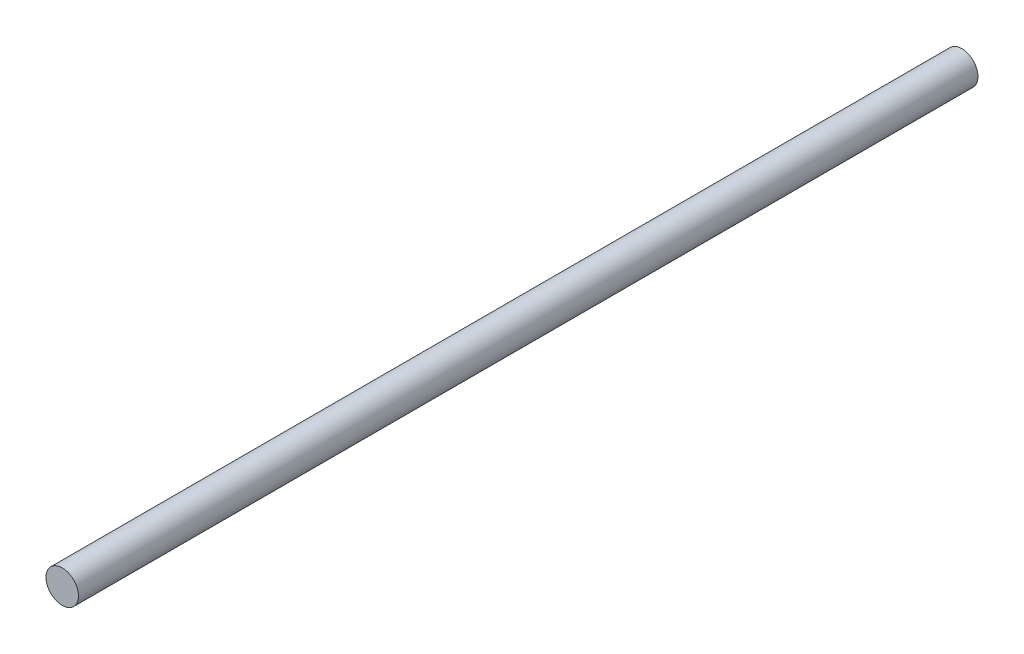
SolidWorks part; units mm, degrees
ref_plane "Front Plane" through (0, 0, 0) normal (1, 0, 0) x (0, 1, 0)
ref_plane "Top Plane" through (0, 0, 0) normal (0, 0, 1) x (0, 1, 0)
ref_plane "Right Plane" through (0, 0, 0) normal (0, 1, 0) x (-1, 0, 0)
sketch "Sketch1" plane through (0, 0, 0) normal (0, 0, 1) x (0, 1, 0)
  circle A0 centre (0, 0) radius 1.5
  dimension "D1" = 3
extrude "Boss-Extrude1" add sketch "Sketch1" along normal blind 83
